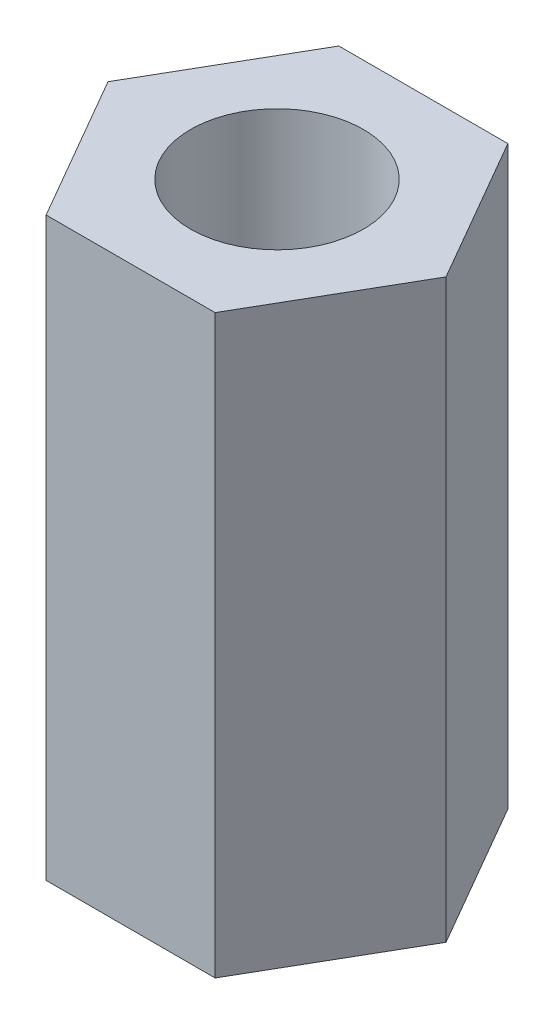
SolidWorks part; units mm, degrees
material "Nylon 101"
ref_plane "Front Plane" through (0, 0, 0) normal (0, 0, 1) x (1, 0, 0)
ref_plane "Top Plane" through (0, 0, 0) normal (0, 1, 0) x (1, 0, 0)
ref_plane "Right Plane" through (0, 0, 0) normal (1, 0, 0) x (0, 0, -1)
sketch "Sketch1" plane through (0, 0, 0) normal (0, 1, 0) x (1, 0, 0)
  line L0 (0, 0) -> (50000, 0) construction
  line L1 (0, 0) -> (0, 50000) construction
  line L2 (1.4665, 2.54) -> (-1.4665, 2.54)
  line L3 (-1.4665, 2.54) -> (-2.9329, 0)
  line L4 (1.4665, 2.54) -> (2.9329, 0)
  line L5 (1.4665, -2.54) -> (2.9329, 0)
  line L6 (-1.4665, -2.54) -> (-2.9329, 0)
  line L7 (1.4665, -2.54) -> (-1.4665, -2.54)
  circle A0 centre (0, 0) radius 1.5
  point P11 (0, 2.54)
  point P14 (0, -2.54)
  point P15 (-1.7951, 3.1605)
  point P16 (1.9986, 3.9568)
  dimension "D1" = 3
  dimension "D2" = 5.08
  dimension "D3" = 5.08
extrude "Boss-Extrude1" add sketch "Sketch1" along normal blind 10
equation "\"D3@Sketch1\"=\"D2@Sketch1\""
